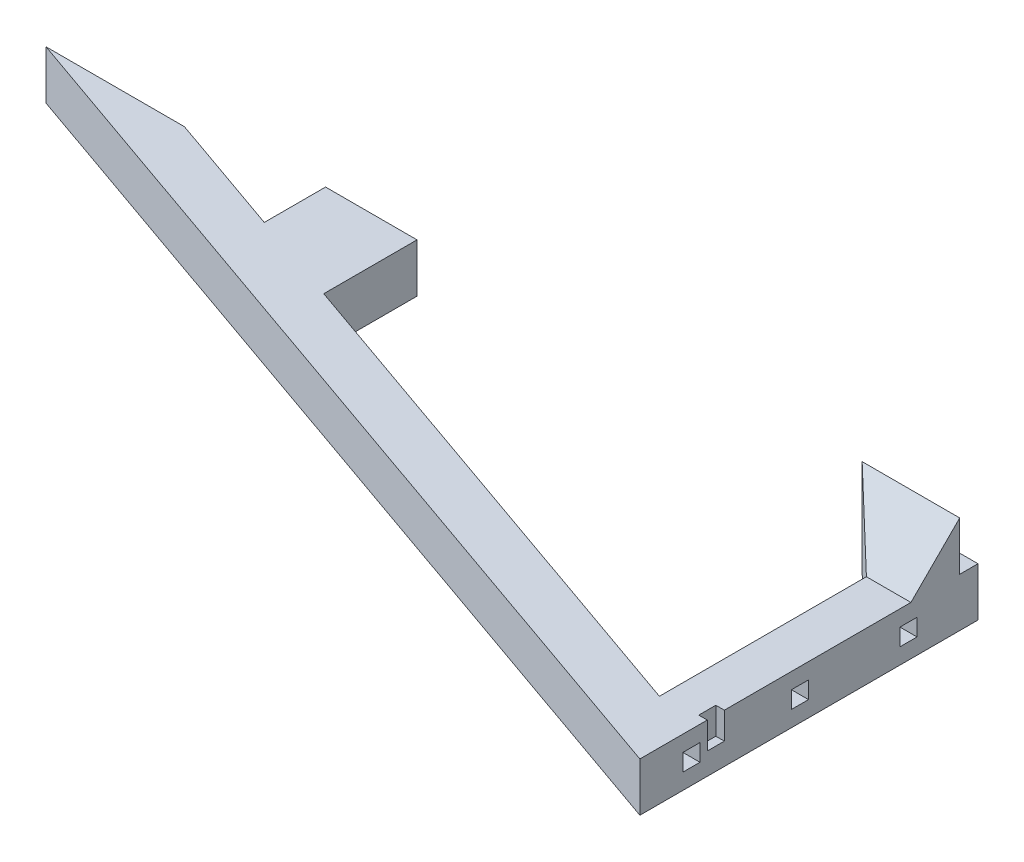
SolidWorks part; units mm, degrees
ref_plane "Přední rovina" through (0, 0, 0) normal (0, 0, 1) x (1, 0, 0)
ref_plane "Horní rovina" through (0, 0, 0) normal (0, 1, 0) x (1, 0, 0)
ref_plane "Pravá rovina" through (0, 0, 0) normal (1, 0, 0) x (0, 0, -1)
sketch "Skica2" plane through (0, 0, 0) normal (0, 1, 0) x (1, 0, 0)
  line L13 (0, 0) -> (0, -55.45)
  line L14 (0, -55.45) -> (-149.85, -3)
  line L15 (-149.85, -3) -> (-127.1478, -3)
  line L16 (-127.1478, -3) -> (-107, -10.0521)
  line L17 (-107, -10.0521) -> (-107, 0)
  line L18 (-107, 0) -> (-92, 0)
  line L19 (-92, 0) -> (-92, -15.3023)
  line L20 (-92, -15.3023) -> (-7.3, -44.9487)
  line L21 (-7.3, -44.9487) -> (-7.3, 0)
  line L22 (-7.3, 0) -> (0, 0)
  point P0 (-9.1908, -42.6671)
  dimension "D1" = 55.45
  dimension "D2" = 149.85
  dimension "D3" = 7.5
  dimension "D4" = 15
  dimension "D5" = 7.3
  dimension "D6" = 3
  dimension "D7" = 7.5
  dimension "D8" = 84.7
extrude "Přidat vysunutím1" add sketch "Skica2" along normal blind 8
sketch "Skica3" plane through (0, 8, 0) normal (0, 1, 0) x (1, 0, 0)
  line L0 (0, -55.45) -> (0, 0) construction
  line L1 (-1.4, -41.6) -> (0, -41.6)
  line L2 (-1.4, -41.6) -> (-1.4, -44.4)
  line L3 (-1.4, -44.4) -> (0, -44.4)
  line L4 (0, -41.6) -> (0, -44.4)
  line L5 (0, 0) -> (-7.3, 0) construction
  dimension "D1" = 1.4
  dimension "D2" = 2.8
  dimension "D3" = 41.6
extrude "Odebrat vysunutím1" cut sketch "Skica3" against normal blind 4.4
sketch "Skica5" plane through (0, 8, 0) normal (0, 1, 0) x (1, 0, 0)
  line L10 (0, -41.6) -> (0, 0) construction
  line L11 (0, -3) -> (-16, -3)
  line L12 (0, -3) -> (0, -11)
  line L13 (0, -11) -> (-16, -11)
  line L14 (-16, -3) -> (-16, -11)
  line L15 (0, 0) -> (-7.3, 0) construction
  dimension "D1" = 3
  dimension "D2" = 8
  dimension "D3" = 16
extrude "Přidat vysunutím2" add sketch "Skica5" against normal blind 16 from offset 8
sketch "Skica6" plane through (0, 0, 0) normal (1, 0, 0) x (0, 0, -1)
  line L3 (-11, 8) -> (-11, 16)
  line L4 (-11, 16) -> (-3, 16)
  line L5 (-3, 16) -> (-11, 8)
extrude "Odebrat vysunutím3" cut sketch "Skica6" against normal through all
sketch "Skica7" plane through (0, 0, 0) normal (0, -1, 0) x (1, 0, 0)
  line L3 (-16, 3) -> (-16, 11)
  line L4 (-16, 11) -> (-7.3, 11)
  line L5 (-7.3, 11) -> (-16, 3)
extrude "Odebrat vysunutím4" cut sketch "Skica7" against normal through all
sketch "Skica4" plane through (0, 0, 0) normal (1, 0, 0) x (0, 0, -1)
  line L0 (-41.6, 8) -> (-11, 8) construction
  line L1 (-48.4, 5.4) -> (-45.6, 5.4)
  line L2 (-48.4, 5.4) -> (-48.4, 2.6)
  line L3 (-48.4, 2.6) -> (-45.6, 2.6)
  line L4 (-45.6, 5.4) -> (-45.6, 2.6)
  line L5 (-30.6, 5.4) -> (-27.8, 5.4)
  line L6 (-30.6, 5.4) -> (-30.6, 2.6)
  line L7 (-30.6, 2.6) -> (-27.8, 2.6)
  line L8 (-27.8, 5.4) -> (-27.8, 2.6)
  line L9 (-12.8, 5.4) -> (-10, 5.4)
  line L10 (-12.8, 5.4) -> (-12.8, 2.6)
  line L11 (-12.8, 2.6) -> (-10, 2.6)
  line L12 (-10, 5.4) -> (-10, 2.6)
  line L13 (-55.45, 8) -> (-44.4, 8) construction
  line L14 (0, 8) -> (0, 0) construction
  dimension "D1" = 2.8
  dimension "D2" = 2.8
  dimension "D3" = 2.8
  dimension "D4" = 2.8
  dimension "D5" = 2.8
  dimension "D6" = 2.8
  dimension "D7" = 2.6
  dimension "D8" = 2.6
  dimension "D9" = 2.6
  dimension "D10" = 10
  dimension "D11" = 15
  dimension "D12" = 15
extrude "Odebrat vysunutím2" cut sketch "Skica4" against normal blind 4.4
